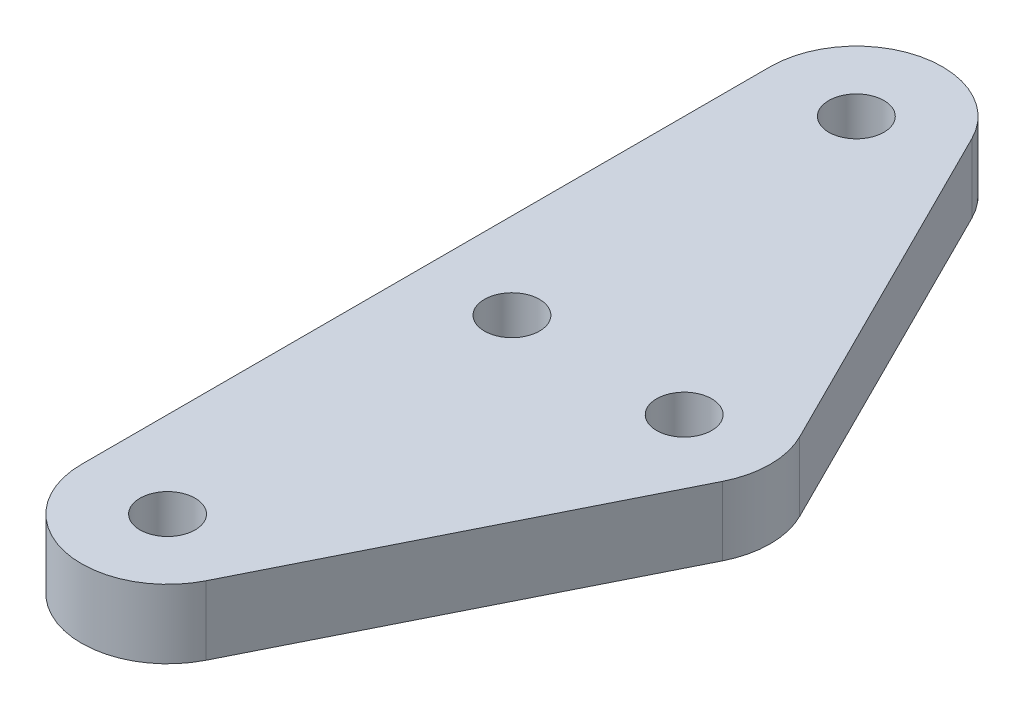
SolidWorks part; units mm, degrees
ref_plane "Спереди" through (0, 0, 0) normal (0, 0, 1) x (1, 0, 0)
ref_plane "Сверху" through (0, 0, 0) normal (0, 1, 0) x (1, 0, 0)
ref_plane "Справа" through (0, 0, 0) normal (1, 0, 0) x (0, 0, -1)
sketch "Sketch1" plane through (0, 0, 0) normal (0, 1, 0) x (1, 0, 0)
  line L0 (0, 20) -> (0, -20) construction
  line L1 (0, 0) -> (10, 0) construction
  line L2 (-5, 20) -> (-5, -20)
  line L3 (4.4721, 22.2361) -> (14.4721, 2.2361)
  line L4 (4.4721, -22.2361) -> (14.4721, -2.2361)
  circle A0 centre (0, 20) radius 1.6
  circle A1 centre (0, -20) radius 1.6
  circle A2 centre (10, 0) radius 1.6
  arc A3 (4.4721, 22.2361) -> (-5, 20) centre (0, 20) ccw
  arc A4 (-5, -20) -> (4.4721, -22.2361) centre (0, -20) ccw
  arc A5 (14.4721, -2.2361) -> (14.4721, 2.2361) centre (10, 0) ccw
  circle A6 centre (0, 0) radius 1.6
  circle A7 centre (0, 0) radius 3.75 construction
  circle A8 centre (10, 0) radius 3.75 construction
  dimension "D2" = 3.2
  dimension "D3" = 7.5
  dimension "D5" = 5
  dimension "D1" = 40
  dimension "D4" = 10
extrude "Boss-Extrude1" add sketch "Sketch1" along normal blind 4
